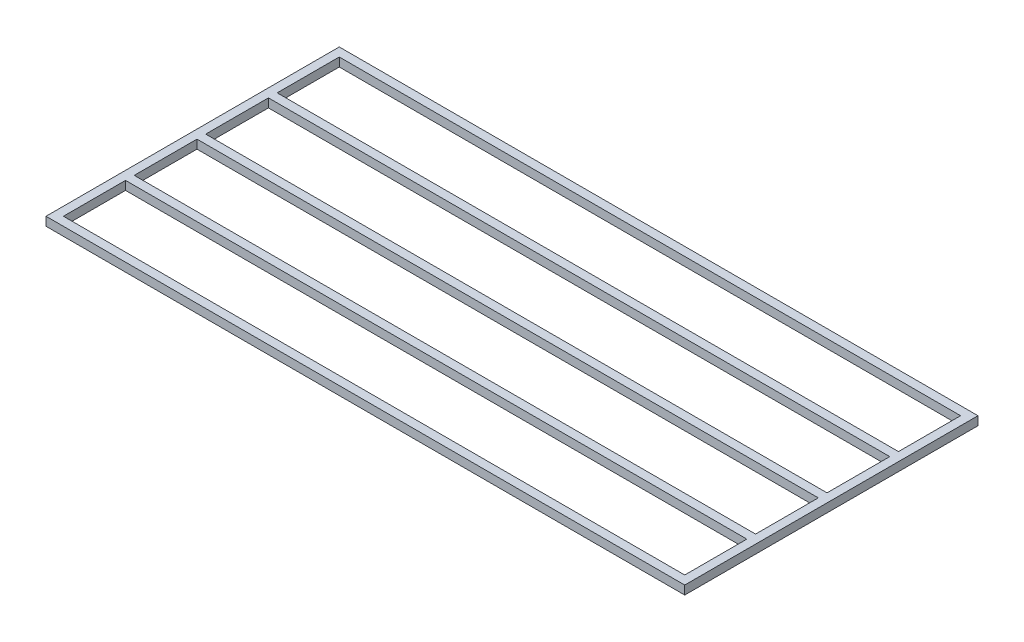
SolidWorks part; units mm, degrees
ref_plane "Front Plane" through (0, 0, 0) normal (0, 0, 1) x (1, 0, 0)
ref_plane "Top Plane" through (0, 0, 0) normal (0, 1, 0) x (1, 0, 0)
ref_plane "Right Plane" through (0, 0, 0) normal (1, 0, 0) x (0, 0, -1)
sketch "Sketch1" plane through (0, 0, 0) normal (0, 1, 0) x (1, 0, 0)
  line L0 (-14, -14) -> (-1014, -14)
  line L1 (0, 0) -> (-1028, 0)
  line L2 (0, 0) -> (0, -472)
  line L3 (0, -472) -> (-1028, -472)
  line L4 (-1028, 0) -> (-1028, -472)
  line L5 (-1014, -14) -> (-1014, -114)
  line L6 (-14, -458) -> (-1014, -458)
  line L7 (-14, -14) -> (-14, -114)
  line L8 (-1014, -128) -> (-1014, -229)
  line L9 (-1014, -114) -> (-14, -114)
  line L11 (-1014, -128) -> (-14, -128)
  line L21 (-1014, -344) -> (-14, -344)
  line L23 (-1014, -358) -> (-14, -358)
  line L25 (-1014, -229) -> (-14, -229)
  line L27 (-1014, -243) -> (-14, -243)
  line L29 (-1014, -14) -> (-1014, -458) construction
  line L30 (-1014, -243) -> (-1014, -344)
  line L31 (-1014, -358) -> (-1014, -458)
  line L32 (-14, -128) -> (-14, -229)
  line L33 (-14, -14) -> (-14, -458) construction
  line L34 (-14, -243) -> (-14, -344)
  line L35 (-14, -358) -> (-14, -458)
  dimension "D1" = 1028
  dimension "D2" = 472
  dimension "D4" = 14
  dimension "D5" = 100
  dimension "D6" = 100
  dimension "D7" = 14
  dimension "D8" = 14
  dimension "D9" = 101
  dimension "D3" = 14
extrude "Boss-Extrude1" add sketch "Sketch1" along normal blind 14 contours L35 L23 L31 L6 | L34 L27 L30 L21 | L32 L11 L8 L25 | L5 L9 L7 L0 | L4 L3 L2 L1
